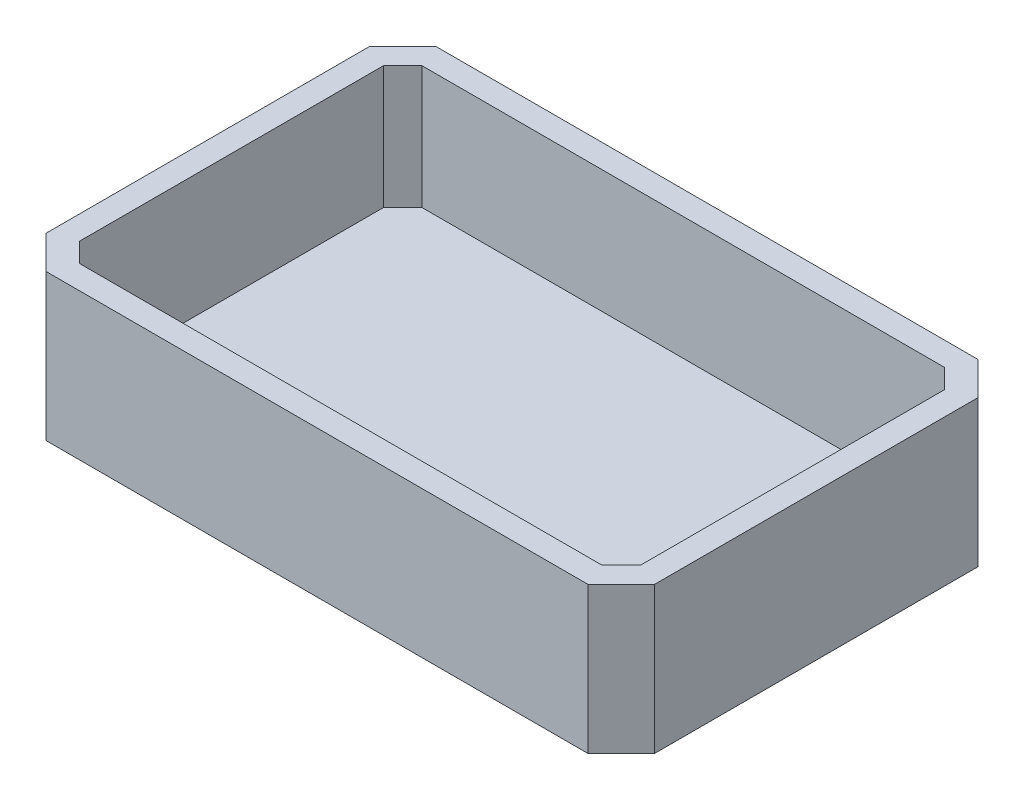
SolidWorks part; units mm, degrees
ref_plane "Front Plane" through (0, 0, 0) normal (0, 0, 1) x (1, 0, 0)
ref_plane "Top Plane" through (0, 0, 0) normal (0, 1, 0) x (1, 0, 0)
ref_plane "Right Plane" through (0, 0, 0) normal (1, 0, 0) x (0, 0, -1)
sketch "Sketch1" plane through (0, 0, 0) normal (0, 1, 0) x (1, 0, 0)
  line L1 (-257.5, -165) -> (257.5, -165)
  line L2 (-257.5, -165) -> (-257.5, 165)
  line L3 (-257.5, 165) -> (257.5, 165)
  line L4 (257.5, -165) -> (257.5, 165)
  line L5 (-257.5, -165) -> (257.5, 165) construction
  line L6 (-257.5, 165) -> (257.5, -165) construction
  point P0 (0, 0)
  dimension "D1" = 515
  dimension "D2" = 330
extrude "Boss-Extrude1" add sketch "Sketch1" along normal blind 124
chamfer "Chamfer1" distance 28 angle 45 4 edges at (257.5, 62, 165) (257.5, 62, -165) (-257.5, 62, -165) (-257.5, 62, 165)
shell "Shell1" thickness 20
